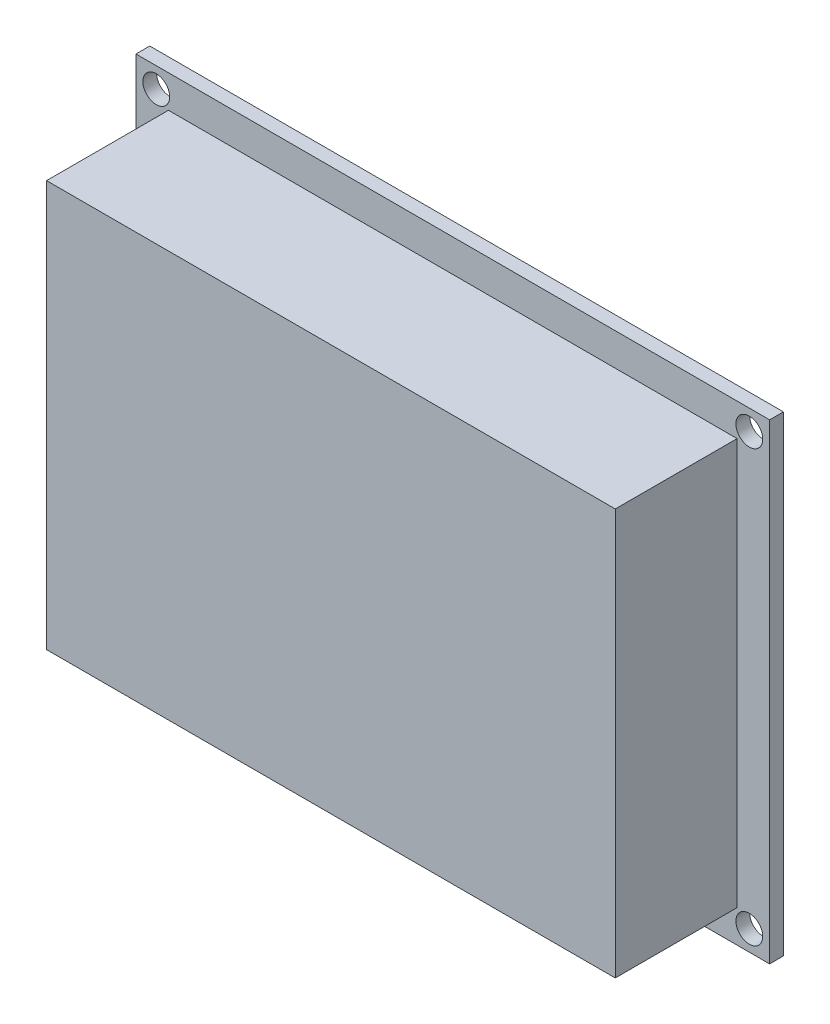
SolidWorks part; units mm, degrees
ref_plane "Plano frontal" through (0, 0, 0) normal (0, 0, 1) x (1, 0, 0)
ref_plane "Plano superior" through (0, 0, 0) normal (0, 1, 0) x (1, 0, 0)
ref_plane "Plano direito" through (0, 0, 0) normal (1, 0, 0) x (0, 0, -1)
sketch "Esboço1" plane through (0, 0, 0) normal (0, 0, 1) x (1, 0, 0)
  line L0 (-39, 29) -> (-39, 26.5) construction
  line L1 (-39, 29) -> (39, 29)
  line L2 (-39, 29) -> (-39, -29)
  line L3 (-39, -29) -> (39, -29)
  line L4 (39, 29) -> (39, -29)
  line L5 (-39, 29) -> (39, -29) construction
  line L6 (-39, -29) -> (39, 29) construction
  line L7 (-39, 26.5) -> (-36.5, 26.5) construction
  line L8 (0, 0) -> (-39, 0) construction
  line L9 (0, 0) -> (0, 29) construction
  circle A0 centre (-36.5, 26.5) radius 1.65
  circle A1 centre (-36.5, -26.5) radius 1.65
  circle A2 centre (36.5, 26.5) radius 1.65
  circle A3 centre (36.5, -26.5) radius 1.65
  point P0 (0, 0)
  dimension "D1" = 78
  dimension "D2" = 58
  dimension "D3" = 2.5
  dimension "D4" = 2.5
extrude "Ressalto-extrusão1" add sketch "Esboço1" along normal blind 1.7
sketch "Esboço2" plane through (0, 0, 1.7) normal (0, 0, 1) x (1, 0, 0)
  line L1 (-35, -25) -> (35, -25)
  line L2 (-35, -25) -> (-35, 25)
  line L3 (-35, 25) -> (35, 25)
  line L4 (35, -25) -> (35, 25)
  line L5 (-35, -25) -> (35, 25) construction
  line L6 (-35, 25) -> (35, -25) construction
  point P0 (0, 0)
  dimension "D1" = 70
  dimension "D2" = 50
extrude "Ressalto-extrusão2" add sketch "Esboço2" along normal blind 15
